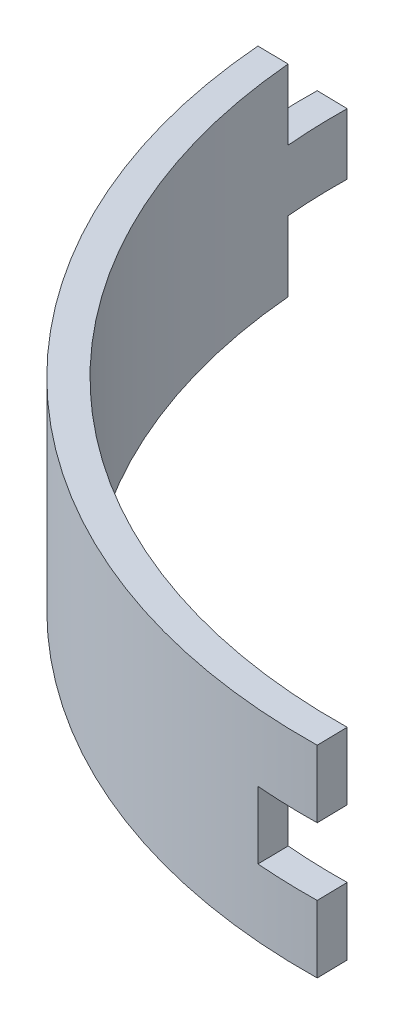
SolidWorks part; units mm, degrees
ref_plane "Front Plane" through (0, 0, 0) normal (0, 0, 1) x (1, 0, 0)
ref_plane "Top Plane" through (0, 0, 0) normal (0, 1, 0) x (1, 0, 0)
ref_plane "Right Plane" through (0, 0, 0) normal (1, 0, 0) x (0, 0, -1)
sketch "Sketch1" plane through (0, 0, 0) normal (0, 1, 0) x (1, 0, 0)
  line L0 (-97.4852, 1.7016) -> (-102.4844, 1.7889)
  line L1 (1.7889, -102.4844) -> (1.7016, -97.4852)
  line L2 (0, 0) -> (0, -102.5) construction
  line L3 (0, 0) -> (-72.4784, -72.4784) construction
  line L4 (-68.9429, -68.9429) -> (-72.4784, -72.4784)
  line L5 (0, 0) -> (-102.5, 0) construction
  arc A1 (-97.4852, 1.7016) -> (1.7016, -97.4852) centre (0, 0) ccw
  arc A2 (-102.4844, 1.7889) -> (1.7889, -102.4844) centre (0, 0) ccw
  point P1 (-68.9429, -68.9429)
  point P21 (0, 0)
  dimension "D4" = 97.5
  dimension "D1" = 5
  dimension "D2" = 45
  dimension "D3" = 92
extrude "Boss-Extrude3" add sketch "Sketch1" along normal blind 33
ref_plane "Plane1" through (0, 0, 0) normal (-0.7071, 0, 0.7071) x (0.7071, 0, 0.7071)
sketch "Sketch3" plane through (0, 0, 0) normal (0.9998, 0, -0.0175) x (-0.0175, 0, -0.9998)
  line L0 (-100, 33) -> (-100, 22)
  line L1 (-102.5, 0) -> (-97.5, 0) construction
  line L3 (-102.5, 33) -> (-97.5, 33) construction
  line L5 (-100, 0) -> (-100, 11)
  line L9 (-94.9015, 22) -> (-105.0985, 22)
  line L10 (-94.9015, 22) -> (-94.9015, 11)
  line L11 (-94.9015, 11) -> (-105.0985, 11)
  line L12 (-105.0985, 22) -> (-105.0985, 11)
  dimension "D2" = 11
  dimension "D3" = 11
sketch "Sketch4" plane through (0, 0, 0) normal (0.0175, 0, -0.9998) x (-0.9998, 0, -0.0175)
  line L0 (100, 33) -> (100, 21.5) construction
  line L1 (97.5, 33) -> (102.5, 33) construction
  line L2 (100, 0) -> (100, 11.5) construction
  line L3 (97.5, 0) -> (102.5, 0) construction
  line L5 (94.0462, 33) -> (105.9538, 33)
  line L6 (94.0462, 33) -> (94.0462, 21.5)
  line L7 (94.0462, 21.5) -> (105.9538, 21.5)
  line L8 (105.9538, 33) -> (105.9538, 21.5)
  line L9 (94.0462, 11.5) -> (105.9538, 11.5)
  line L10 (94.0462, 11.5) -> (94.0462, 0)
  line L11 (94.0462, 0) -> (105.9538, 0)
  line L12 (105.9538, 11.5) -> (105.9538, 0)
  line M6 (97.5, 0) -> (102.5, 0)
  line M7 (102.5, 0) -> (102.5, 33)
  line M9 (97.5, 33) -> (97.5, 0)
  dimension "D1" = 11.5
  dimension "D2" = 11.5
extrude "Cut-Extrude1" cut sketch "Sketch3" against normal blind 10 contours L10 L11 L12 L9
extrude "Cut-Extrude2" cut sketch "Sketch4" against normal blind 10.0075 contours L12 L9 L11 M7 | L10 L11 L9 M9 | L9 M9 M6 M7 | L8 L7 L6 L5
equation "\"D1@Boss-Extrude3\"=\"ringH@ring assembly.Assembly\""
equation "\"D1\"= 2"
equation "\"D4@Sketch1\"=\"innerD@ring assembly.Assembly\"/2"
equation "\"D1@Cut-Extrude2\"=\"RD1@Annotations\""
equation "\"D3@Sketch3\"=\"D2@Sketch3\""
equation "\"D1@Sketch4\"=\"D2@Sketch3\"+0.5"
equation "\"D2@Sketch4\"=\"D3@Sketch3\"+0.5"
